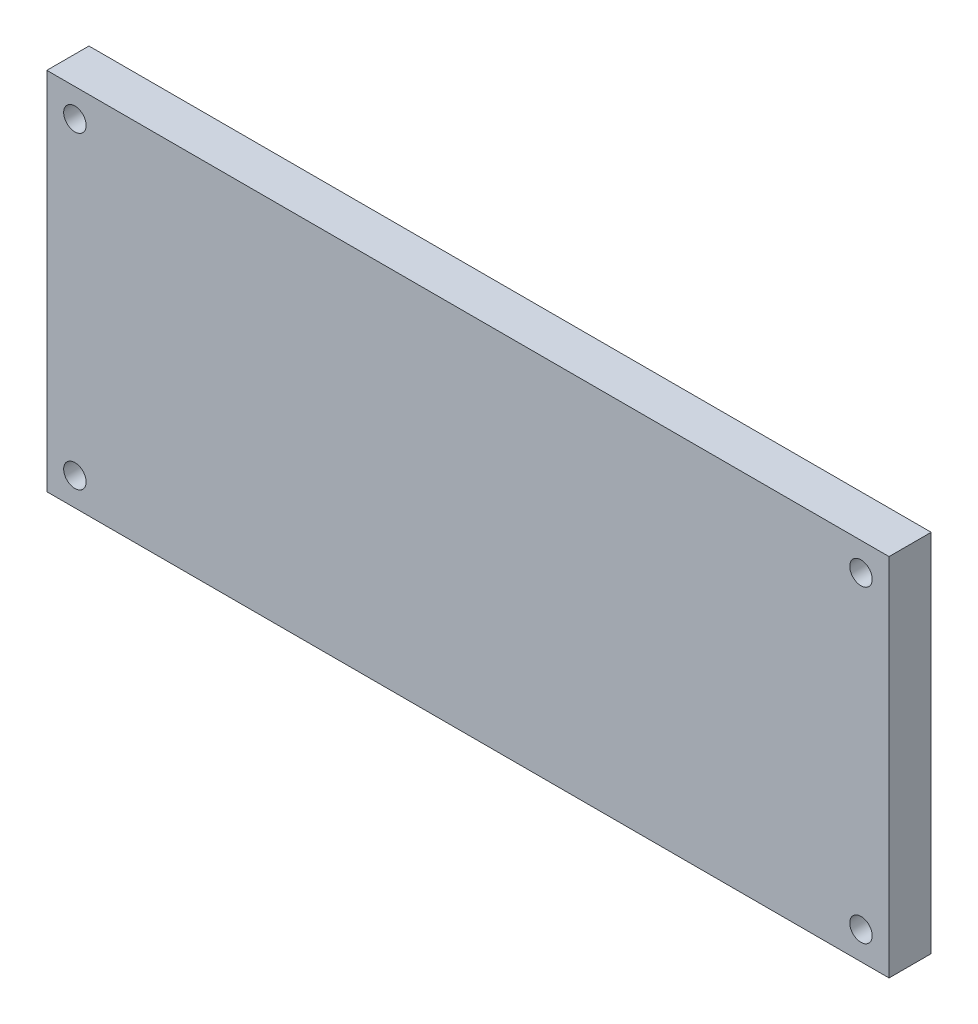
SolidWorks part; units mm, degrees
ref_plane "Plan de face" through (0, 0, 0) normal (0, 0, 1) x (1, 0, 0)
ref_plane "Plan de dessus" through (0, 0, 0) normal (0, 1, 0) x (1, 0, 0)
ref_plane "Plan de droite" through (0, 0, 0) normal (1, 0, 0) x (0, 0, -1)
sketch "Esquisse1" plane through (0, 0, 0) normal (0, 0, 1) x (1, 0, 0)
  line L0 (-393.8027, 0) -> (-93.8027, 0)
  line L1 (-93.8027, 0) -> (-93.8027, 130)
  line L2 (-93.8027, 130) -> (-393.8027, 130)
  line L3 (-393.8027, 130) -> (-393.8027, 0)
  dimension "D1" = 300
  dimension "D2" = 130
extrude "Boss.-Extru.1" add sketch "Esquisse1" along normal blind 15
sketch "Esquisse2" plane through (0, 0, 15) normal (0, 0, 1) x (1, 0, 0)
  circle A0 centre (-383.8027, 120) radius 4
  point P2 (0, 0)
  point P3 (0, 0)
sketch "Esquisse3" plane through (0, 0, 15) normal (0, 0, 1) x (1, 0, 0)
  circle A0 centre (-383.8027, 10) radius 4
  circle A1 centre (-103.8027, 120) radius 4
  circle A2 centre (-103.8027, 10) radius 4
extrude "Enlèv. mat.-Extru.2" cut sketch "Esquisse2" against normal through all contours A0
extrude "Enlèv. mat.-Extru.3" cut sketch "Esquisse3" against normal through all contours A2
sketch "Esquisse5" plane through (0, 0, 0) normal (0, 0, -1) x (-1, 0, 0)
  circle A0 centre (103.8027, 120) radius 4
  circle A2 centre (383.8027, 10) radius 4
extrude "Enlèv. mat.-Extru.4" cut sketch "Esquisse5" against normal through all
